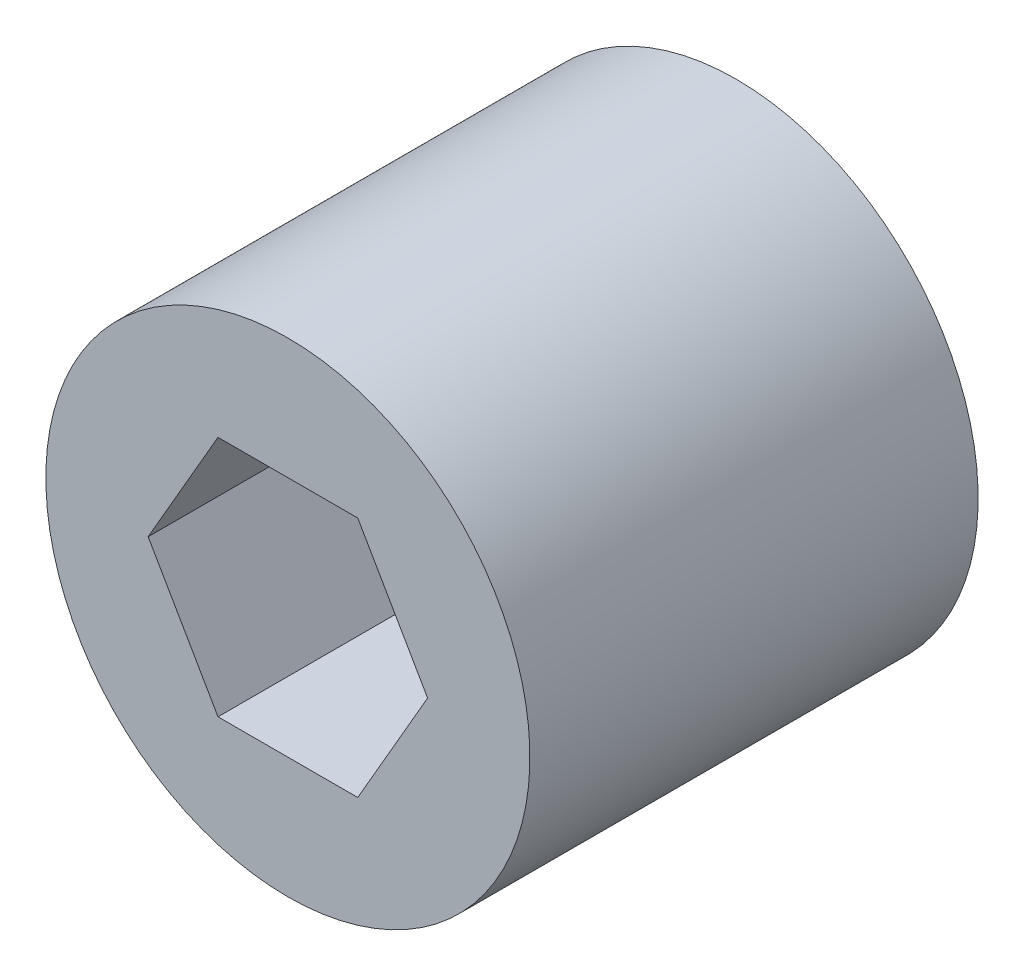
SolidWorks part; units mm, degrees
material "Delrin 2700 NC010, Low Viscosity Acetal Copolymer (SS)"
ref_plane "Front Plane" through (0, 0, 0) normal (0, 0, 1) x (1, 0, 0)
ref_plane "Top Plane" through (0, 0, 0) normal (0, 1, 0) x (1, 0, 0)
ref_plane "Right Plane" through (0, 0, 0) normal (1, 0, 0) x (0, 0, -1)
sketch "Sketch1" plane through (0, 0, 0) normal (1, 0, 0) x (0, 0, -1)
  line L1 (0, 0) -> (23.5204, 0)
  line L2 (0, 8.286) -> (0, 12.7)
  line L3 (0, 12.7) -> (23.5204, 12.7)
  line L4 (23.5204, 8.286) -> (23.5204, 12.7)
  line L5 (0, 8.286) -> (0, 0)
  line L6 (11.7602, 12.7) -> (11.7602, 0) construction
  line L8 (23.5204, 8.286) -> (23.5204, 0)
  line L9 (0, 8.286) -> (23.5204, 8.286) construction
  line L10 (0, 8.286) -> (0, 0) construction
  dimension "D1" = 12.7
  dimension "D2" = 23.5204
revolve "Revolve1" add sketch "Sketch1" angle 360 about L1
sketch "Sketch2" plane through (0, 0, 0) normal (0, 0, 1) x (1, 0, 0)
  line L1 (3.6662, 6.35) -> (-3.6662, 6.35)
  line L2 (-3.6662, 6.35) -> (-7.3323, 0)
  line L3 (-7.3323, 0) -> (-3.6662, -6.35)
  line L4 (-3.6662, -6.35) -> (3.6662, -6.35)
  line L5 (3.6662, -6.35) -> (7.3323, 0)
  line L6 (7.3323, 0) -> (3.6662, 6.35)
  circle A0 centre (0, 0) radius 6.35 construction
  dimension "D1" = 12.7
extrude "Cut-Extrude1" cut sketch "Sketch2" against normal through all
